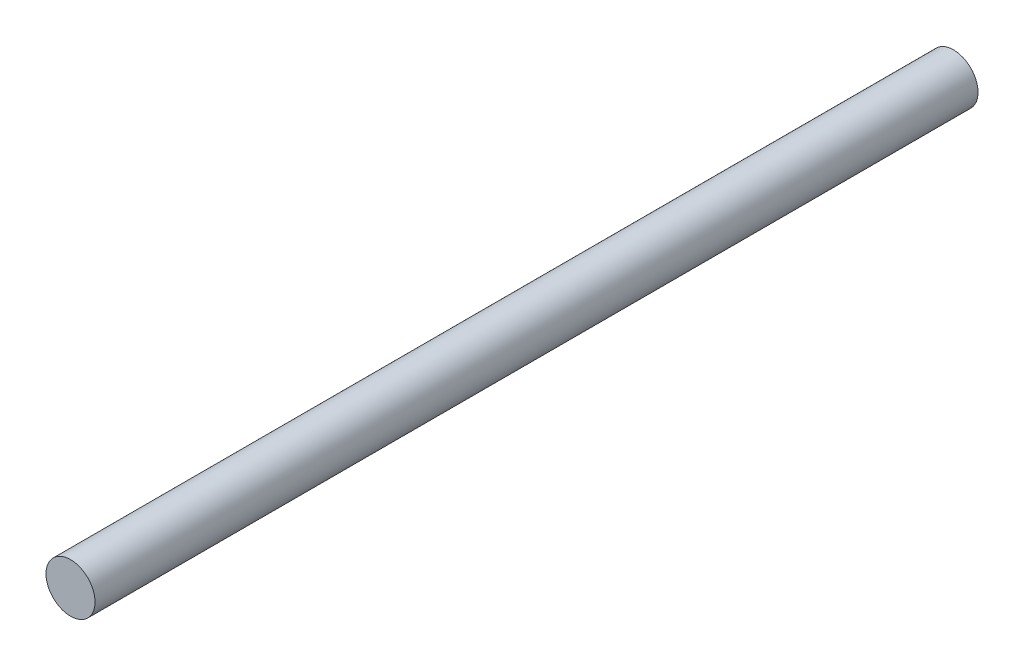
SolidWorks part; units mm, degrees
ref_plane "Płaszczyzna przednia" through (0, 0, 0) normal (0, 0, 1) x (1, 0, 0)
ref_plane "Płaszczyzna górna" through (0, 0, 0) normal (0, 1, 0) x (1, 0, 0)
ref_plane "Płaszczyzna prawa" through (0, 0, 0) normal (1, 0, 0) x (0, 0, -1)
sketch "Szkic1" plane through (0, 0, 0) normal (0, 0, 1) x (1, 0, 0)
  circle A0 centre (0, 0) radius 5
extrude "Dodanie-wyciągnięcie1" add sketch "Szkic1" along normal blind 180
